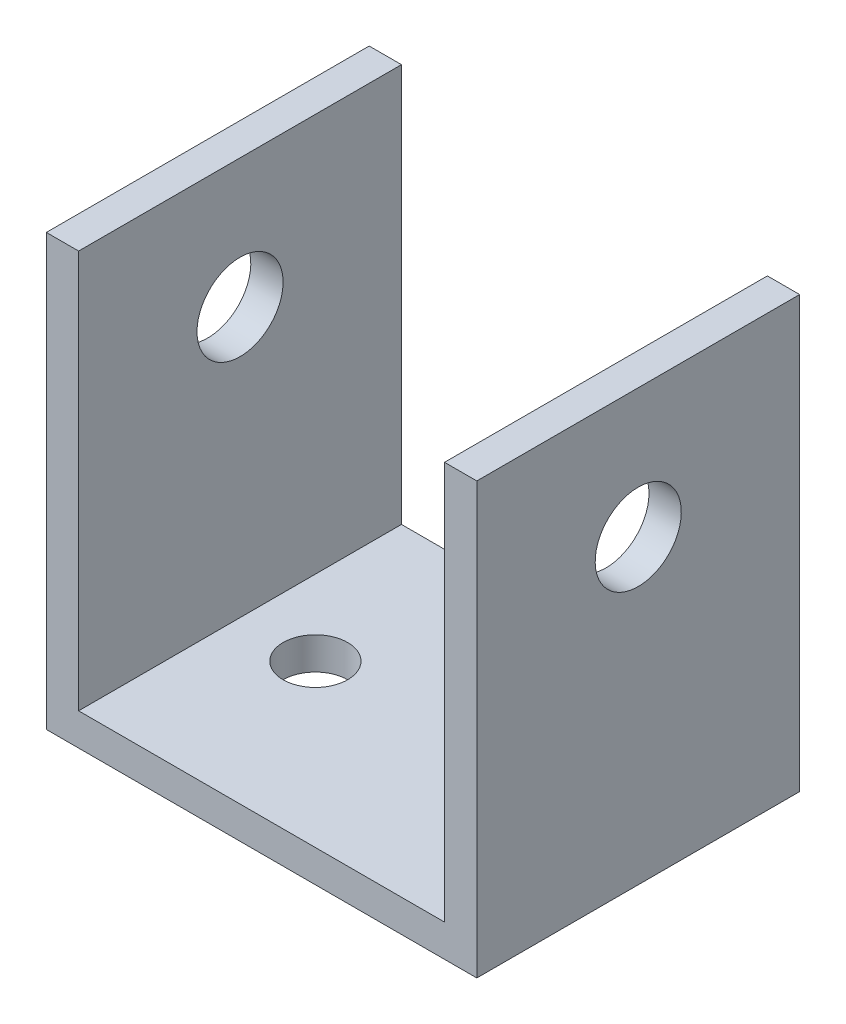
SolidWorks part; units mm, degrees
ref_plane "Plan de face" through (0, 0, 0) normal (0, 0, 1) x (1, 0, 0)
ref_plane "Plan de dessus" through (0, 0, 0) normal (0, 1, 0) x (1, 0, 0)
ref_plane "Plan de droite" through (0, 0, 0) normal (1, 0, 0) x (0, 0, -1)
sketch "Esquisse1" plane through (0, 0, 0) normal (0, 0, 1) x (1, 0, 0)
  line L0 (-1.5, 17.7265) -> (-1.5, -2.2735)
  line L1 (-1.5, -2.2735) -> (18.5, -2.2735)
  line L2 (0, -0.7735) -> (17, -0.7735)
  line L3 (17, -0.7735) -> (17, 17.7265)
  line L4 (0, -0.7735) -> (0, 17.7265)
  line L5 (0, 17.7265) -> (-1.5, 17.7265)
  line L6 (17, 17.7265) -> (18.5, 17.7265)
  line L7 (18.5, 17.7265) -> (18.5, -2.2735)
  dimension "D1" = 1.5
  dimension "D2" = 20
  dimension "D3" = 20
  dimension "D4" = 20
  dimension "D5" = 1.5
  dimension "D6" = 1.5
extrude "Extrusion1" add sketch "Esquisse1" along normal blind 15
sketch "Esquisse3" plane through (18.5, 0, 0) normal (1, 0, 0) x (0, 0, -1)
  line L0 (-15, 17.7265) -> (0, 17.7265) construction
  line L1 (0, -2.2735) -> (0, 17.7265) construction
  circle A0 centre (-7.5, 11.7265) radius 2
  point P2 (-7.5, 17.7265)
  dimension "D1" = 6
  dimension "D2" = 7.5
extrude "Extrusion3" cut sketch "Esquisse3" against normal through all
sketch "Esquisse4" plane through (0, -0.7735, 0) normal (0, 1, 0) x (1, 0, 0)
  line L0 (3.5, -7.5) -> (13.5, -7.5) construction
  line L1 (18.5, -15) -> (18.5, 0) construction
  line L2 (17, 0) -> (0, 0) construction
  circle A0 centre (3.5, -7.5) radius 1.5
  circle A1 centre (13.5, -7.5) radius 1.5
  point P4 (18.5, -7.5)
  dimension "D1" = 10
  dimension "D2" = 5
  dimension "D3" = 7.5
extrude "Extrusion4" cut sketch "Esquisse4" against normal blind 10
